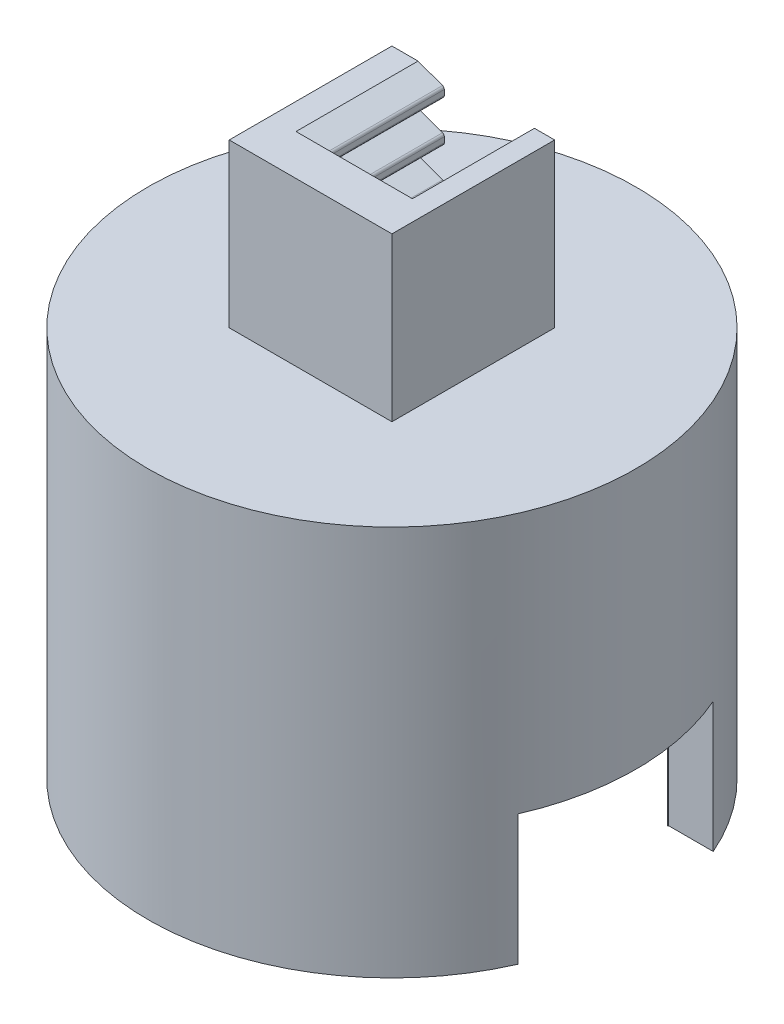
SolidWorks part; units mm, degrees
ref_plane "Front Plane" through (0, 0, 0) normal (0, 0, 1) x (1, 0, 0)
ref_plane "Top Plane" through (0, 0, 0) normal (0, 1, 0) x (1, 0, 0)
ref_plane "Right Plane" through (0, 0, 0) normal (1, 0, 0) x (0, 0, -1)
sketch "Sketch1" plane through (0, 0, 0) normal (0, 1, 0) x (1, 0, 0)
  circle A0 centre (0, 0) radius 15
  circle A1 centre (0, 0) radius 12.5
  dimension "D1" = 25
  dimension "D2" = 30
extrude "Boss-Extrude1" add sketch "Sketch1" along normal blind 20
sketch "Sketch2" plane through (0, 20, 0) normal (0, 1, 0) x (1, 0, 0)
  circle A0 centre (0, 0) radius 15
extrude "Boss-Extrude2" add sketch "Sketch2" along normal blind 4
ref_plane "Plane1" through (15, 0, 0) normal (1, 0, 0) x (0, 0, -1)
sketch "Sketch3" plane through (15, 0, 0) normal (1, 0, 0) x (0, 0, -1)
  line L0 (-15, 0) -> (15, 0) construction
  line L1 (-6, 0) -> (6, 0)
  line L2 (-6, 0) -> (-6, 8)
  line L3 (-6, 8) -> (6, 8)
  line L4 (6, 0) -> (6, 8)
  line L5 (0, 24) -> (0, 0) construction
  line L6 (15, 24) -> (-15, 24) construction
  dimension "D1" = 12
  dimension "D2" = 8
extrude "Cut-Extrude1" cut sketch "Sketch3" against normal blind 4
sketch "Sketch4" plane through (0, 24, 0) normal (0, 1, 0) x (1, 0, 0)
  line L0 (0, 5) -> (0, -5) construction
  line L1 (-5, 5) -> (5, 5)
  line L2 (-5, 5) -> (-5, -5)
  line L3 (-5, -5) -> (5, -5)
  line L4 (5, 5) -> (5, -5)
  line L5 (-5, 0) -> (5, 0) construction
  dimension "D1" = 10
  dimension "D2" = 10
extrude "Boss-Extrude3" add sketch "Sketch4" along normal blind 10
sketch "Sketch6" plane through (0, 0, -5) normal (0, 0, -1) x (-1, 0, 0)
  line L1 (-5, 34) -> (5, 34) construction
  line L3 (-3.7584, 34) -> (3.3958, 34)
  line L4 (-3.7584, 24) -> (3.5416, 24)
  line L405 (2.1355, 274) -> (0.2416, 274)
  line L406 (0.2416, 274) -> (0.2416, 34)
  line L407 (0.2416, 34) -> (-1.7584, 34)
  line L408 (-1.7584, 34) -> (-1.7584, 274)
  line L409 (-1.7584, 274) -> (-3.7584, 274)
  line L410 (-3.7584, 274) -> (-3.7584, 24)
  line L411 (-3.7584, 24) -> (3.5416, 24)
  line L412 (3.5416, 24) -> (3.5416, 24.6743)
  line L413 (3.5416, 24.6743) -> (1.8918, 25.2748)
  line L414 (1.7816, 25.432) -> (1.7816, 25.7555)
  line L415 (1.8918, 25.9128) -> (3.5416, 26.5133)
  line L416 (3.5416, 26.5133) -> (3.5416, 27.1876)
  line L417 (3.5416, 27.1876) -> (1.8918, 27.7881)
  line L418 (1.7816, 27.9453) -> (1.7816, 28.2688)
  line L419 (1.8918, 28.426) -> (3.5416, 29.0265)
  line L420 (3.5416, 29.0265) -> (3.5416, 29.7008)
  line L421 (3.5416, 29.7008) -> (1.8918, 30.3013)
  line L422 (1.7816, 30.4586) -> (1.7816, 30.7821)
  line L423 (1.8918, 30.9393) -> (3.5416, 31.5398)
  line L424 (3.5416, 31.5398) -> (3.5416, 32.2141)
  line L425 (3.5416, 32.2141) -> (1.8918, 32.8146)
  line L426 (1.7816, 32.9719) -> (1.7816, 33.2953)
  line L427 (1.8918, 33.4526) -> (3.5416, 34.0531)
  line L428 (3.5416, 34.0531) -> (3.5416, 34.7274)
  line L429 (3.5416, 34.7274) -> (1.8918, 35.3279)
  line L430 (1.7816, 35.4851) -> (1.7816, 35.8086)
  line L431 (1.8918, 35.9658) -> (3.5416, 36.5664)
  line L432 (3.5416, 36.5664) -> (3.5416, 37.2406)
  line L433 (3.5416, 37.2406) -> (1.8918, 37.8412)
  line L434 (1.7816, 37.9984) -> (1.7816, 38.3219)
  line L435 (1.8918, 38.4791) -> (3.5416, 39.0796)
  line L436 (3.5416, 39.0796) -> (3.5416, 39.7539)
  line L437 (3.5416, 39.7539) -> (1.8918, 40.3544)
  line L438 (1.7816, 40.5117) -> (1.7816, 40.8351)
  line L439 (1.8918, 40.9924) -> (3.5416, 41.5929)
  line L440 (3.5416, 41.5929) -> (3.5416, 42.2672)
  line L441 (3.5416, 42.2672) -> (1.8918, 42.8677)
  line L442 (1.7816, 43.025) -> (1.7816, 43.3484)
  line L443 (1.8918, 43.5057) -> (3.5416, 44.1062)
  line L444 (3.5416, 44.1062) -> (3.5416, 44.7805)
  line L445 (3.5416, 44.7805) -> (1.8918, 45.381)
  line L446 (1.7816, 45.5382) -> (1.7816, 45.8617)
  line L447 (1.8918, 46.0189) -> (3.5416, 46.6194)
  line L448 (3.5416, 46.6194) -> (3.5416, 47.2937)
  line L449 (3.5416, 47.2937) -> (1.8918, 47.8942)
  line L450 (1.7816, 48.0515) -> (1.7816, 48.375)
  line L451 (1.8918, 48.5322) -> (3.5416, 49.1327)
  line L452 (3.5416, 49.1327) -> (3.5416, 49.807)
  line L453 (3.5416, 49.807) -> (1.8918, 50.4075)
  line L454 (1.7816, 50.5648) -> (1.7816, 50.8882)
  line L455 (1.8918, 51.0455) -> (3.5416, 51.646)
  line L456 (3.5416, 51.646) -> (3.5416, 52.3203)
  line L457 (3.5416, 52.3203) -> (1.8918, 52.9208)
  line L458 (1.7816, 53.078) -> (1.7816, 53.4015)
  line L459 (1.8918, 53.5588) -> (3.5416, 54.1593)
  line L460 (3.5416, 54.1593) -> (3.5416, 54.8335)
  line L461 (3.5416, 54.8335) -> (1.8918, 55.4341)
  line L462 (1.7816, 55.5913) -> (1.7816, 55.9148)
  line L463 (1.8918, 56.072) -> (3.5416, 56.6725)
  line L464 (3.5416, 56.6725) -> (3.5416, 57.3468)
  line L465 (3.5416, 57.3468) -> (1.8918, 57.9473)
  line L466 (1.7816, 58.1046) -> (1.7816, 58.428)
  line L467 (1.8918, 58.5853) -> (3.5416, 59.1858)
  line L468 (3.5416, 59.1858) -> (3.5416, 59.8601)
  line L469 (3.5416, 59.8601) -> (1.8918, 60.4606)
  line L470 (1.7816, 60.6179) -> (1.7816, 60.9413)
  line L471 (1.8918, 61.0986) -> (3.5416, 61.6991)
  line L472 (3.5416, 61.6991) -> (3.5416, 62.3734)
  line L473 (3.5416, 62.3734) -> (1.8918, 62.9739)
  line L474 (1.7816, 63.1311) -> (1.7816, 63.4546)
  line L475 (1.8918, 63.6118) -> (3.5416, 64.2124)
  line L476 (3.5416, 64.2124) -> (3.5416, 64.8866)
  line L477 (3.5416, 64.8866) -> (1.8918, 65.4871)
  line L478 (1.7816, 65.6444) -> (1.7816, 65.9679)
  line L479 (1.8918, 66.1251) -> (3.5416, 66.7256)
  line L480 (3.5416, 66.7256) -> (3.5416, 67.3999)
  line L481 (3.5416, 67.3999) -> (1.8918, 68.0004)
  line L482 (1.7816, 68.1577) -> (1.7816, 68.4811)
  line L483 (1.8918, 68.6384) -> (3.5416, 69.2389)
  line L484 (3.5416, 69.2389) -> (3.5416, 69.9132)
  line L485 (3.5416, 69.9132) -> (1.8918, 70.5137)
  line L486 (1.7816, 70.6709) -> (1.7816, 70.9944)
  line L487 (1.8918, 71.1517) -> (3.5416, 71.7522)
  line L488 (3.5416, 71.7522) -> (3.5416, 72.4265)
  line L489 (3.5416, 72.4265) -> (1.8918, 73.027)
  line L490 (1.7816, 73.1842) -> (1.7816, 73.5077)
  line L491 (1.8918, 73.6649) -> (3.5416, 74.2654)
  line L492 (3.5416, 74.2654) -> (3.5416, 74.9397)
  line L493 (3.5416, 74.9397) -> (1.8918, 75.5402)
  line L494 (1.7816, 75.6975) -> (1.7816, 76.0209)
  line L495 (1.8918, 76.1782) -> (3.5416, 76.7787)
  line L496 (3.5416, 76.7787) -> (3.5416, 77.453)
  line L497 (3.5416, 77.453) -> (1.8918, 78.0535)
  line L498 (1.7816, 78.2108) -> (1.7816, 78.5342)
  line L499 (1.8918, 78.6915) -> (3.5416, 79.292)
  line L500 (3.5416, 79.292) -> (3.5416, 79.9663)
  line L501 (3.5416, 79.9663) -> (1.8918, 80.5668)
  line L502 (1.7816, 80.724) -> (1.7816, 81.0475)
  line L503 (1.8918, 81.2047) -> (3.5416, 81.8053)
  line L504 (3.5416, 81.8053) -> (3.5416, 82.4795)
  line L505 (3.5416, 82.4795) -> (1.8918, 83.0801)
  line L506 (1.7816, 83.2373) -> (1.7816, 83.5608)
  line L507 (1.8918, 83.718) -> (3.5416, 84.3185)
  line L508 (3.5416, 84.3185) -> (3.5416, 84.9928)
  line L509 (3.5416, 84.9928) -> (1.8918, 85.5933)
  line L510 (1.7816, 85.7506) -> (1.7816, 86.074)
  line L511 (1.8918, 86.2313) -> (3.5416, 86.8318)
  line L512 (3.5416, 86.8318) -> (3.5416, 87.5061)
  line L513 (3.5416, 87.5061) -> (1.8918, 88.1066)
  line L514 (1.7816, 88.2638) -> (1.7816, 88.5873)
  line L515 (1.8918, 88.7446) -> (3.5416, 89.3451)
  line L516 (3.5416, 89.3451) -> (3.5416, 90.0194)
  line L517 (3.5416, 90.0194) -> (1.8918, 90.6199)
  line L518 (1.7816, 90.7771) -> (1.7816, 91.1006)
  line L519 (1.8918, 91.2578) -> (3.5416, 91.8583)
  line L520 (3.5416, 91.8583) -> (3.5416, 92.5326)
  line L521 (3.5416, 92.5326) -> (1.8918, 93.1331)
  line L522 (1.7816, 93.2904) -> (1.7816, 93.6139)
  line L523 (1.8918, 93.7711) -> (3.5416, 94.3716)
  line L524 (3.5416, 94.3716) -> (3.5416, 95.0459)
  line L525 (3.5416, 95.0459) -> (1.8918, 95.6464)
  line L526 (1.7816, 95.8037) -> (1.7816, 96.1271)
  line L527 (1.8918, 96.2844) -> (3.5416, 96.8849)
  line L528 (3.5416, 96.8849) -> (3.5416, 97.5592)
  line L529 (3.5416, 97.5592) -> (1.8918, 98.1597)
  line L530 (1.7816, 98.3169) -> (1.7816, 98.6404)
  line L531 (1.8918, 98.7976) -> (3.5416, 99.3982)
  line L532 (3.5416, 99.3982) -> (3.5416, 100.0724)
  line L533 (3.5416, 100.0724) -> (1.8918, 100.673)
  line L534 (1.7816, 100.8302) -> (1.7816, 101.1537)
  line L535 (1.8918, 101.3109) -> (3.5416, 101.9114)
  line L536 (3.5416, 101.9114) -> (3.5416, 102.5857)
  line L537 (3.5416, 102.5857) -> (1.8918, 103.1862)
  line L538 (1.7816, 103.3435) -> (1.7816, 103.6669)
  line L539 (1.8918, 103.8242) -> (3.5416, 104.4247)
  line L540 (3.5416, 104.4247) -> (3.5416, 105.099)
  line L541 (3.5416, 105.099) -> (1.8918, 105.6995)
  line L542 (1.7816, 105.8568) -> (1.7816, 106.1802)
  line L543 (1.8918, 106.3375) -> (3.5416, 106.938)
  line L544 (3.5416, 106.938) -> (3.5416, 107.6123)
  line L545 (3.5416, 107.6123) -> (1.8918, 108.2128)
  line L546 (1.7816, 108.37) -> (1.7816, 108.6935)
  line L547 (1.8918, 108.8507) -> (3.5416, 109.4512)
  line L548 (3.5416, 109.4512) -> (3.5416, 110.1255)
  line L549 (3.5416, 110.1255) -> (1.8918, 110.726)
  line L550 (1.7816, 110.8833) -> (1.7816, 111.2068)
  line L551 (1.8918, 111.364) -> (3.5416, 111.9645)
  line L552 (3.5416, 111.9645) -> (3.5416, 112.6388)
  line L553 (3.5416, 112.6388) -> (1.8918, 113.2393)
  line L554 (1.7816, 113.3966) -> (1.7816, 113.72)
  line L555 (1.8918, 113.8773) -> (3.5416, 114.4778)
  line L556 (3.5416, 114.4778) -> (3.5416, 115.1521)
  line L557 (3.5416, 115.1521) -> (1.8918, 115.7526)
  line L558 (1.7816, 115.9098) -> (1.7816, 116.2333)
  line L559 (1.8918, 116.3906) -> (3.5416, 116.9911)
  line L560 (3.5416, 116.9911) -> (3.5416, 117.6653)
  line L561 (3.5416, 117.6653) -> (1.8918, 118.2659)
  line L562 (1.7816, 118.4231) -> (1.7816, 118.7466)
  line L563 (1.8918, 118.9038) -> (3.5416, 119.5043)
  line L564 (3.5416, 119.5043) -> (3.5416, 120.1786)
  line L565 (3.5416, 120.1786) -> (1.8918, 120.7791)
  line L566 (1.7816, 120.9364) -> (1.7816, 121.2598)
  line L567 (1.8918, 121.4171) -> (3.5416, 122.0176)
  line L568 (3.5416, 122.0176) -> (3.5416, 122.6919)
  line L569 (3.5416, 122.6919) -> (1.8918, 123.2924)
  line L570 (1.7816, 123.4497) -> (1.7816, 123.7731)
  line L571 (1.8918, 123.9304) -> (3.5416, 124.5309)
  line L572 (3.5416, 124.5309) -> (3.5416, 125.2052)
  line L573 (3.5416, 125.2052) -> (1.8918, 125.8057)
  line L574 (1.7816, 125.9629) -> (1.7816, 126.2864)
  line L575 (1.8918, 126.4436) -> (3.5416, 127.0442)
  line L576 (3.5416, 127.0442) -> (3.5416, 127.7184)
  line L577 (3.5416, 127.7184) -> (1.8918, 128.3189)
  line L578 (1.7816, 128.4762) -> (1.7816, 128.7997)
  line L579 (1.8918, 128.9569) -> (3.5416, 129.5574)
  line L580 (3.5416, 129.5574) -> (3.5416, 130.2317)
  line L581 (3.5416, 130.2317) -> (1.8918, 130.8322)
  line L582 (1.7816, 130.9895) -> (1.7816, 131.3129)
  line L583 (1.8918, 131.4702) -> (3.5416, 132.0707)
  line L584 (3.5416, 132.0707) -> (3.5416, 132.745)
  line L585 (3.5416, 132.745) -> (1.8918, 133.3455)
  line L586 (1.7816, 133.5027) -> (1.7816, 133.8262)
  line L587 (1.8918, 133.9835) -> (3.5416, 134.584)
  line L588 (3.5416, 134.584) -> (3.5416, 135.2583)
  line L589 (3.5416, 135.2583) -> (1.8918, 135.8588)
  line L590 (1.7816, 136.016) -> (1.7816, 136.3395)
  line L591 (1.8918, 136.4967) -> (3.5416, 137.0972)
  line L592 (3.5416, 137.0972) -> (3.5416, 137.7715)
  line L593 (3.5416, 137.7715) -> (1.8918, 138.372)
  line L594 (1.7816, 138.5293) -> (1.7816, 138.8527)
  line L595 (1.8918, 139.01) -> (3.5416, 139.6105)
  line L596 (3.5416, 139.6105) -> (3.5416, 140.2848)
  line L597 (3.5416, 140.2848) -> (1.8918, 140.8853)
  line L598 (1.7816, 141.0426) -> (1.7816, 141.366)
  line L599 (1.8918, 141.5233) -> (3.5416, 142.1238)
  line L600 (3.5416, 142.1238) -> (3.5416, 142.7981)
  line L601 (3.5416, 142.7981) -> (1.8918, 143.3986)
  line L602 (1.7816, 143.5558) -> (1.7816, 143.8793)
  line L603 (1.8918, 144.0365) -> (3.5416, 144.6371)
  line L604 (3.5416, 144.6371) -> (3.5416, 145.3113)
  line L605 (3.5416, 145.3113) -> (1.8918, 145.9119)
  line L606 (1.7816, 146.0691) -> (1.7816, 146.3926)
  line L607 (1.8918, 146.5498) -> (3.5416, 147.1503)
  line L608 (3.5416, 147.1503) -> (3.5416, 147.8246)
  line L609 (3.5416, 147.8246) -> (1.8918, 148.4251)
  line L610 (1.7816, 148.5824) -> (1.7816, 148.9058)
  line L611 (1.8918, 149.0631) -> (3.5416, 149.6636)
  line L612 (3.5416, 149.6636) -> (3.5416, 150.3379)
  line L613 (3.5416, 150.3379) -> (1.8918, 150.9384)
  line L614 (1.7816, 151.0956) -> (1.7816, 151.4191)
  line L615 (1.8918, 151.5764) -> (3.5416, 152.1769)
  line L616 (3.5416, 152.1769) -> (3.5416, 152.8512)
  line L617 (3.5416, 152.8512) -> (1.8918, 153.4517)
  line L618 (1.7816, 153.6089) -> (1.7816, 153.9324)
  line L619 (1.8918, 154.0896) -> (3.5416, 154.6901)
  line L620 (3.5416, 154.6901) -> (3.5416, 155.3644)
  line L621 (3.5416, 155.3644) -> (1.8918, 155.9649)
  line L622 (1.7816, 156.1222) -> (1.7816, 156.4457)
  line L623 (1.8918, 156.6029) -> (3.5416, 157.2034)
  line L624 (3.5416, 157.2034) -> (3.5416, 157.8777)
  line L625 (3.5416, 157.8777) -> (1.8918, 158.4782)
  line L626 (1.7816, 158.6355) -> (1.7816, 158.9589)
  line L627 (1.8918, 159.1162) -> (3.5416, 159.7167)
  line L628 (3.5416, 159.7167) -> (3.5416, 160.391)
  line L629 (3.5416, 160.391) -> (1.8918, 160.9915)
  line L630 (1.7816, 161.1487) -> (1.7816, 161.4722)
  line L631 (1.8918, 161.6294) -> (3.5416, 162.23)
  line L632 (3.5416, 162.23) -> (3.5416, 162.9042)
  line L633 (3.5416, 162.9042) -> (1.8918, 163.5048)
  line L634 (1.7816, 163.662) -> (1.7816, 163.9855)
  line L635 (1.8918, 164.1427) -> (3.5416, 164.7432)
  line L636 (3.5416, 164.7432) -> (3.5416, 165.4175)
  line L637 (3.5416, 165.4175) -> (1.8918, 166.018)
  line L638 (1.7816, 166.1753) -> (1.7816, 166.4987)
  line L639 (1.8918, 166.656) -> (3.5416, 167.2565)
  line L640 (3.5416, 167.2565) -> (3.5416, 167.9308)
  line L641 (3.5416, 167.9308) -> (1.8918, 168.5313)
  line L642 (1.7816, 168.6886) -> (1.7816, 169.012)
  line L643 (1.8918, 169.1693) -> (3.5416, 169.7698)
  line L644 (3.5416, 169.7698) -> (3.5416, 170.4441)
  line L645 (3.5416, 170.4441) -> (1.8918, 171.0446)
  line L646 (1.7816, 171.2018) -> (1.7816, 171.5253)
  line L647 (1.8918, 171.6825) -> (3.5416, 172.283)
  line L648 (3.5416, 172.283) -> (3.5416, 172.9573)
  line L649 (3.5416, 172.9573) -> (1.8918, 173.5578)
  line L650 (1.7816, 173.7151) -> (1.7816, 174.0386)
  line L651 (1.8918, 174.1958) -> (3.5416, 174.7963)
  line L652 (3.5416, 174.7963) -> (3.5416, 175.4706)
  line L653 (3.5416, 175.4706) -> (1.8918, 176.0711)
  line L654 (1.7816, 176.2284) -> (1.7816, 176.5518)
  line L655 (1.8918, 176.7091) -> (3.5416, 177.3096)
  line L656 (3.5416, 177.3096) -> (3.5416, 177.9839)
  line L657 (3.5416, 177.9839) -> (1.8918, 178.5844)
  line L658 (1.7816, 178.7416) -> (1.7816, 179.0651)
  line L659 (1.8918, 179.2224) -> (3.5416, 179.8229)
  line L660 (3.5416, 179.8229) -> (3.5416, 180.4971)
  line L661 (3.5416, 180.4971) -> (1.8918, 181.0977)
  line L662 (1.7816, 181.2549) -> (1.7816, 181.5784)
  line L663 (1.8918, 181.7356) -> (3.5416, 182.3361)
  line L664 (3.5416, 182.3361) -> (3.5416, 183.0104)
  line L665 (3.5416, 183.0104) -> (1.8918, 183.6109)
  line L666 (1.7816, 183.7682) -> (1.7816, 184.0916)
  line L667 (1.8918, 184.2489) -> (3.5416, 184.8494)
  line L668 (3.5416, 184.8494) -> (3.5416, 185.5237)
  line L669 (3.5416, 185.5237) -> (1.8918, 186.1242)
  line L670 (1.7816, 186.2815) -> (1.7816, 186.6049)
  line L671 (1.8918, 186.7622) -> (3.5416, 187.3627)
  line L672 (3.5416, 187.3627) -> (3.5416, 188.037)
  line L673 (3.5416, 188.037) -> (1.8918, 188.6375)
  line L674 (1.7816, 188.7947) -> (1.7816, 189.1182)
  line L675 (1.8918, 189.2754) -> (3.5416, 189.876)
  line L676 (3.5416, 189.876) -> (3.5416, 190.5502)
  line L677 (3.5416, 190.5502) -> (1.8918, 191.1507)
  line L678 (1.7816, 191.308) -> (1.7816, 191.6315)
  line L679 (1.8918, 191.7887) -> (3.5416, 192.3892)
  line L680 (3.5416, 192.3892) -> (3.5416, 193.0635)
  line L681 (3.5416, 193.0635) -> (1.8918, 193.664)
  line L682 (1.7816, 193.8213) -> (1.7816, 194.1447)
  line L683 (1.8918, 194.302) -> (3.5416, 194.9025)
  line L684 (3.5416, 194.9025) -> (3.5416, 195.5768)
  line L685 (3.5416, 195.5768) -> (1.8918, 196.1773)
  line L686 (1.7816, 196.3345) -> (1.7816, 196.658)
  line L687 (1.8918, 196.8153) -> (3.5416, 197.4158)
  line L688 (3.5416, 197.4158) -> (3.5416, 198.0901)
  line L689 (3.5416, 198.0901) -> (1.8918, 198.6906)
  line L690 (1.7816, 198.8478) -> (1.7816, 199.1713)
  line L691 (1.8918, 199.3285) -> (3.5416, 199.929)
  line L692 (3.5416, 199.929) -> (3.5416, 200.6033)
  line L693 (3.5416, 200.6033) -> (1.8918, 201.2038)
  line L694 (1.7816, 201.3611) -> (1.7816, 201.6845)
  line L695 (1.8918, 201.8418) -> (3.5416, 202.4423)
  line L696 (3.5416, 202.4423) -> (3.5416, 203.1166)
  line L697 (3.5416, 203.1166) -> (1.8918, 203.7171)
  line L698 (1.7816, 203.8744) -> (1.7816, 204.1978)
  line L699 (1.8918, 204.3551) -> (3.5416, 204.9556)
  line L700 (3.5416, 204.9556) -> (3.5416, 205.6299)
  line L701 (3.5416, 205.6299) -> (1.8918, 206.2304)
  line L702 (1.7816, 206.3876) -> (1.7816, 206.7111)
  line L703 (1.8918, 206.8683) -> (3.5416, 207.4689)
  line L704 (3.5416, 207.4689) -> (3.5416, 208.1431)
  line L705 (3.5416, 208.1431) -> (1.8918, 208.7437)
  line L706 (1.7816, 208.9009) -> (1.7816, 209.2244)
  line L707 (1.8918, 209.3816) -> (3.5416, 209.9821)
  line L708 (3.5416, 209.9821) -> (3.5416, 210.6564)
  line L709 (3.5416, 210.6564) -> (1.8918, 211.2569)
  line L710 (1.7816, 211.4142) -> (1.7816, 211.7376)
  line L711 (1.8918, 211.8949) -> (3.5416, 212.4954)
  line L712 (3.5416, 212.4954) -> (3.5416, 213.1697)
  line L713 (3.5416, 213.1697) -> (1.8918, 213.7702)
  line L714 (1.7816, 213.9274) -> (1.7816, 214.2509)
  line L715 (1.8918, 214.4082) -> (3.5416, 215.0087)
  line L716 (3.5416, 215.0087) -> (3.5416, 215.683)
  line L717 (3.5416, 215.683) -> (1.8918, 216.2835)
  line L718 (1.7816, 216.4407) -> (1.7816, 216.7642)
  line L719 (1.8918, 216.9214) -> (3.5416, 217.5219)
  line L720 (3.5416, 217.5219) -> (3.5416, 218.1962)
  line L721 (3.5416, 218.1962) -> (1.8918, 218.7967)
  line L722 (1.7816, 218.954) -> (1.7816, 219.2775)
  line L723 (1.8918, 219.4347) -> (3.5416, 220.0352)
  line L724 (3.5416, 220.0352) -> (3.5416, 220.7095)
  line L725 (3.5416, 220.7095) -> (1.8918, 221.31)
  line L726 (1.7816, 221.4673) -> (1.7816, 221.7907)
  line L727 (1.8918, 221.948) -> (3.5416, 222.5485)
  line L728 (3.5416, 222.5485) -> (3.5416, 223.2228)
  line L729 (3.5416, 223.2228) -> (1.8918, 223.8233)
  line L730 (1.7816, 223.9805) -> (1.7816, 224.304)
  line L731 (1.8918, 224.4612) -> (3.5416, 225.0618)
  line L732 (3.5416, 225.0618) -> (3.5416, 225.736)
  line L733 (3.5416, 225.736) -> (1.8918, 226.3366)
  line L734 (1.7816, 226.4938) -> (1.7816, 226.8173)
  line L735 (1.8918, 226.9745) -> (3.5416, 227.575)
  line L736 (3.5416, 227.575) -> (3.5416, 228.2493)
  line L737 (3.5416, 228.2493) -> (1.8918, 228.8498)
  line L738 (1.7816, 229.0071) -> (1.7816, 229.3305)
  line L739 (1.8918, 229.4878) -> (3.5416, 230.0883)
  line L740 (3.5416, 230.0883) -> (3.5416, 230.7626)
  line L741 (3.5416, 230.7626) -> (1.8918, 231.3631)
  line L742 (1.7816, 231.5204) -> (1.7816, 231.8438)
  line L743 (1.8918, 232.0011) -> (3.5416, 232.6016)
  line L744 (3.5416, 232.6016) -> (3.5416, 233.2759)
  line L745 (3.5416, 233.2759) -> (1.8918, 233.8764)
  line L746 (1.7816, 234.0336) -> (1.7816, 234.3571)
  line L747 (1.8918, 234.5143) -> (3.5416, 235.1148)
  line L748 (3.5416, 235.1148) -> (3.5416, 235.7891)
  line L749 (3.5416, 235.7891) -> (1.8918, 236.3896)
  line L750 (1.7816, 236.5469) -> (1.7816, 236.8704)
  line L751 (1.8918, 237.0276) -> (3.5416, 237.6281)
  line L752 (3.5416, 237.6281) -> (3.5416, 238.3024)
  line L753 (3.5416, 238.3024) -> (1.8918, 238.9029)
  line L754 (1.7816, 239.0602) -> (1.7816, 239.3836)
  line L755 (1.8918, 239.5409) -> (3.5416, 240.1414)
  line L756 (3.5416, 240.1414) -> (3.5416, 240.8157)
  line L757 (3.5416, 240.8157) -> (1.8918, 241.4162)
  line L758 (1.7816, 241.5734) -> (1.7816, 241.8969)
  line L759 (1.8918, 242.0542) -> (3.5416, 242.6547)
  line L760 (3.5416, 242.6547) -> (3.5416, 243.3289)
  line L761 (3.5416, 243.3289) -> (1.8918, 243.9295)
  line L762 (1.7816, 244.0867) -> (1.7816, 244.4102)
  line L763 (1.8918, 244.5674) -> (3.5416, 245.1679)
  line L764 (3.5416, 245.1679) -> (3.5416, 245.8422)
  line L765 (3.5416, 245.8422) -> (1.8918, 246.4427)
  line L766 (1.7816, 246.6) -> (1.7816, 246.9234)
  line L767 (1.8918, 247.0807) -> (3.5416, 247.6812)
  line L768 (3.5416, 247.6812) -> (3.5416, 248.3555)
  line L769 (3.5416, 248.3555) -> (1.8918, 248.956)
  line L770 (1.7816, 249.1133) -> (1.7816, 249.4367)
  line L771 (1.8918, 249.594) -> (3.5416, 250.1945)
  line L772 (3.5416, 250.1945) -> (3.5416, 250.8688)
  line L773 (3.5416, 250.8688) -> (1.8918, 251.4693)
  line L774 (1.7816, 251.6265) -> (1.7816, 251.95)
  line L775 (1.8918, 252.1072) -> (3.5416, 252.7078)
  line L776 (3.5416, 252.7078) -> (3.5416, 253.382)
  line L777 (3.5416, 253.382) -> (1.8918, 253.9825)
  line L778 (1.7816, 254.1398) -> (1.7816, 254.4633)
  line L779 (1.8918, 254.6205) -> (3.5416, 255.221)
  line L780 (3.5416, 255.221) -> (3.5416, 255.8953)
  line L781 (3.5416, 255.8953) -> (1.8918, 256.4958)
  line L782 (1.7816, 256.6531) -> (1.7816, 256.9765)
  line L783 (1.8918, 257.1338) -> (3.5416, 257.7343)
  line L784 (3.5416, 257.7343) -> (3.5416, 258.4086)
  line L785 (3.5416, 258.4086) -> (1.8918, 259.0091)
  line L786 (1.7816, 259.1663) -> (1.7816, 259.4898)
  line L787 (1.8918, 259.6471) -> (3.5416, 260.2476)
  line L788 (3.5416, 260.2476) -> (3.5416, 260.9219)
  line L789 (3.5416, 260.9219) -> (1.8918, 261.5224)
  line L790 (1.7816, 261.6796) -> (1.7816, 262.0031)
  line L791 (1.8918, 262.1603) -> (3.5416, 262.7608)
  line L792 (3.5416, 262.7608) -> (3.5416, 263.4351)
  line L793 (3.5416, 263.4351) -> (1.8918, 264.0356)
  line L794 (1.7816, 264.1929) -> (1.7816, 264.5163)
  line L795 (1.8918, 264.6736) -> (3.5416, 265.2741)
  line L796 (3.5416, 265.2741) -> (3.5416, 265.9484)
  line L797 (3.5416, 265.9484) -> (1.8918, 266.5489)
  line L798 (1.7816, 266.7062) -> (1.7816, 267.0296)
  line L799 (1.8918, 267.1869) -> (3.5416, 267.7874)
  line L800 (3.5416, 267.7874) -> (3.5416, 268.4617)
  line L801 (3.5416, 268.4617) -> (1.8918, 269.0622)
  line L802 (1.7816, 269.2194) -> (1.7816, 269.5429)
  line L803 (1.8918, 269.7001) -> (3.5416, 270.3007)
  line L804 (3.5416, 270.3007) -> (3.5416, 270.9749)
  line L805 (3.5416, 270.9749) -> (1.8918, 271.5755)
  line L806 (1.7816, 271.7327) -> (1.7816, 272.0562)
  line L807 (1.8918, 272.2134) -> (3.5416, 272.8139)
  line L808 (3.5416, 272.8139) -> (3.5416, 273.4882)
  line L809 (3.5416, 273.4882) -> (2.1355, 274)
  line L815 (-3.7584, 34) -> (-3.7584, 24)
  line L816 (-3.7584, 24) -> (3.5416, 24)
  line L817 (3.5416, 24) -> (3.5416, 24.6743)
  line L818 (3.5416, 24.6743) -> (1.8918, 25.2748)
  line L819 (1.7816, 25.432) -> (1.7816, 25.7555)
  line L820 (1.8918, 25.9128) -> (3.5416, 26.5133)
  line L821 (3.5416, 26.5133) -> (3.5416, 27.1876)
  line L822 (3.5416, 27.1876) -> (1.8918, 27.7881)
  line L823 (1.7816, 27.9453) -> (1.7816, 28.2688)
  line L824 (1.8918, 28.426) -> (3.5416, 29.0265)
  line L825 (3.5416, 29.0265) -> (3.5416, 29.7008)
  line L826 (3.5416, 29.7008) -> (1.8918, 30.3013)
  line L827 (1.7816, 30.4586) -> (1.7816, 30.7821)
  line L828 (1.8918, 30.9393) -> (3.5416, 31.5398)
  line L829 (3.5416, 31.5398) -> (3.5416, 32.2141)
  line L830 (3.5416, 32.2141) -> (1.8918, 32.8146)
  line L831 (1.7816, 32.9719) -> (1.7816, 33.2953)
  line L832 (1.8918, 33.4526) -> (3.3958, 34)
  arc A198 (1.7816, 25.432) -> (1.8918, 25.2748) centre (1.949, 25.432) ccw
  arc A199 (1.8918, 25.9128) -> (1.7816, 25.7555) centre (1.949, 25.7555) ccw
  arc A200 (1.7816, 27.9453) -> (1.8918, 27.7881) centre (1.949, 27.9453) ccw
  arc A201 (1.8918, 28.426) -> (1.7816, 28.2688) centre (1.949, 28.2688) ccw
  arc A202 (1.7816, 30.4586) -> (1.8918, 30.3013) centre (1.949, 30.4586) ccw
  arc A203 (1.8918, 30.9393) -> (1.7816, 30.7821) centre (1.949, 30.7821) ccw
  arc A204 (1.7816, 32.9719) -> (1.8918, 32.8146) centre (1.949, 32.9719) ccw
  arc A205 (1.8918, 33.4526) -> (1.7816, 33.2953) centre (1.949, 33.2953) ccw
  arc A206 (1.7816, 35.4851) -> (1.8918, 35.3279) centre (1.949, 35.4851) ccw
  arc A207 (1.8918, 35.9658) -> (1.7816, 35.8086) centre (1.949, 35.8086) ccw
  arc A208 (1.7816, 37.9984) -> (1.8918, 37.8412) centre (1.949, 37.9984) ccw
  arc A209 (1.8918, 38.4791) -> (1.7816, 38.3219) centre (1.949, 38.3219) ccw
  arc A210 (1.7816, 40.5117) -> (1.8918, 40.3544) centre (1.949, 40.5117) ccw
  arc A211 (1.8918, 40.9924) -> (1.7816, 40.8351) centre (1.949, 40.8351) ccw
  arc A212 (1.7816, 43.025) -> (1.8918, 42.8677) centre (1.949, 43.025) ccw
  arc A213 (1.8918, 43.5057) -> (1.7816, 43.3484) centre (1.949, 43.3484) ccw
  arc A214 (1.7816, 45.5382) -> (1.8918, 45.381) centre (1.949, 45.5382) ccw
  arc A215 (1.8918, 46.0189) -> (1.7816, 45.8617) centre (1.949, 45.8617) ccw
  arc A216 (1.7816, 48.0515) -> (1.8918, 47.8942) centre (1.949, 48.0515) ccw
  arc A217 (1.8918, 48.5322) -> (1.7816, 48.375) centre (1.949, 48.375) ccw
  arc A218 (1.7816, 50.5648) -> (1.8918, 50.4075) centre (1.949, 50.5648) ccw
  arc A219 (1.8918, 51.0455) -> (1.7816, 50.8882) centre (1.949, 50.8882) ccw
  arc A220 (1.7816, 53.078) -> (1.8918, 52.9208) centre (1.949, 53.078) ccw
  arc A221 (1.8918, 53.5588) -> (1.7816, 53.4015) centre (1.949, 53.4015) ccw
  arc A222 (1.7816, 55.5913) -> (1.8918, 55.4341) centre (1.949, 55.5913) ccw
  arc A223 (1.8918, 56.072) -> (1.7816, 55.9148) centre (1.949, 55.9148) ccw
  arc A224 (1.7816, 58.1046) -> (1.8918, 57.9473) centre (1.949, 58.1046) ccw
  arc A225 (1.8918, 58.5853) -> (1.7816, 58.428) centre (1.949, 58.428) ccw
  arc A226 (1.7816, 60.6179) -> (1.8918, 60.4606) centre (1.949, 60.6179) ccw
  arc A227 (1.8918, 61.0986) -> (1.7816, 60.9413) centre (1.949, 60.9413) ccw
  arc A228 (1.7816, 63.1311) -> (1.8918, 62.9739) centre (1.949, 63.1311) ccw
  arc A229 (1.8918, 63.6118) -> (1.7816, 63.4546) centre (1.949, 63.4546) ccw
  arc A230 (1.7816, 65.6444) -> (1.8918, 65.4871) centre (1.949, 65.6444) ccw
  arc A231 (1.8918, 66.1251) -> (1.7816, 65.9679) centre (1.949, 65.9679) ccw
  arc A232 (1.7816, 68.1577) -> (1.8918, 68.0004) centre (1.949, 68.1577) ccw
  arc A233 (1.8918, 68.6384) -> (1.7816, 68.4811) centre (1.949, 68.4811) ccw
  arc A234 (1.7816, 70.6709) -> (1.8918, 70.5137) centre (1.949, 70.6709) ccw
  arc A235 (1.8918, 71.1517) -> (1.7816, 70.9944) centre (1.949, 70.9944) ccw
  arc A236 (1.7816, 73.1842) -> (1.8918, 73.027) centre (1.949, 73.1842) ccw
  arc A237 (1.8918, 73.6649) -> (1.7816, 73.5077) centre (1.949, 73.5077) ccw
  arc A238 (1.7816, 75.6975) -> (1.8918, 75.5402) centre (1.949, 75.6975) ccw
  arc A239 (1.8918, 76.1782) -> (1.7816, 76.0209) centre (1.949, 76.0209) ccw
  arc A240 (1.7816, 78.2108) -> (1.8918, 78.0535) centre (1.949, 78.2108) ccw
  arc A241 (1.8918, 78.6915) -> (1.7816, 78.5342) centre (1.949, 78.5342) ccw
  arc A242 (1.7816, 80.724) -> (1.8918, 80.5668) centre (1.949, 80.724) ccw
  arc A243 (1.8918, 81.2047) -> (1.7816, 81.0475) centre (1.949, 81.0475) ccw
  arc A244 (1.7816, 83.2373) -> (1.8918, 83.0801) centre (1.949, 83.2373) ccw
  arc A245 (1.8918, 83.718) -> (1.7816, 83.5608) centre (1.949, 83.5608) ccw
  arc A246 (1.7816, 85.7506) -> (1.8918, 85.5933) centre (1.949, 85.7506) ccw
  arc A247 (1.8918, 86.2313) -> (1.7816, 86.074) centre (1.949, 86.074) ccw
  arc A248 (1.7816, 88.2638) -> (1.8918, 88.1066) centre (1.949, 88.2638) ccw
  arc A249 (1.8918, 88.7446) -> (1.7816, 88.5873) centre (1.949, 88.5873) ccw
  arc A250 (1.7816, 90.7771) -> (1.8918, 90.6199) centre (1.949, 90.7771) ccw
  arc A251 (1.8918, 91.2578) -> (1.7816, 91.1006) centre (1.949, 91.1006) ccw
  arc A252 (1.7816, 93.2904) -> (1.8918, 93.1331) centre (1.949, 93.2904) ccw
  arc A253 (1.8918, 93.7711) -> (1.7816, 93.6139) centre (1.949, 93.6139) ccw
  arc A254 (1.7816, 95.8037) -> (1.8918, 95.6464) centre (1.949, 95.8037) ccw
  arc A255 (1.8918, 96.2844) -> (1.7816, 96.1271) centre (1.949, 96.1271) ccw
  arc A256 (1.7816, 98.3169) -> (1.8918, 98.1597) centre (1.949, 98.3169) ccw
  arc A257 (1.8918, 98.7976) -> (1.7816, 98.6404) centre (1.949, 98.6404) ccw
  arc A258 (1.7816, 100.8302) -> (1.8918, 100.673) centre (1.949, 100.8302) ccw
  arc A259 (1.8918, 101.3109) -> (1.7816, 101.1537) centre (1.949, 101.1537) ccw
  arc A260 (1.7816, 103.3435) -> (1.8918, 103.1862) centre (1.949, 103.3435) ccw
  arc A261 (1.8918, 103.8242) -> (1.7816, 103.6669) centre (1.949, 103.6669) ccw
  arc A262 (1.7816, 105.8568) -> (1.8918, 105.6995) centre (1.949, 105.8568) ccw
  arc A263 (1.8918, 106.3375) -> (1.7816, 106.1802) centre (1.949, 106.1802) ccw
  arc A264 (1.7816, 108.37) -> (1.8918, 108.2128) centre (1.949, 108.37) ccw
  arc A265 (1.8918, 108.8507) -> (1.7816, 108.6935) centre (1.949, 108.6935) ccw
  arc A266 (1.7816, 110.8833) -> (1.8918, 110.726) centre (1.949, 110.8833) ccw
  arc A267 (1.8918, 111.364) -> (1.7816, 111.2068) centre (1.949, 111.2068) ccw
  arc A268 (1.7816, 113.3966) -> (1.8918, 113.2393) centre (1.949, 113.3966) ccw
  arc A269 (1.8918, 113.8773) -> (1.7816, 113.72) centre (1.949, 113.72) ccw
  arc A270 (1.7816, 115.9098) -> (1.8918, 115.7526) centre (1.949, 115.9098) ccw
  arc A271 (1.8918, 116.3906) -> (1.7816, 116.2333) centre (1.949, 116.2333) ccw
  arc A272 (1.7816, 118.4231) -> (1.8918, 118.2659) centre (1.949, 118.4231) ccw
  arc A273 (1.8918, 118.9038) -> (1.7816, 118.7466) centre (1.949, 118.7466) ccw
  arc A274 (1.7816, 120.9364) -> (1.8918, 120.7791) centre (1.949, 120.9364) ccw
  arc A275 (1.8918, 121.4171) -> (1.7816, 121.2598) centre (1.949, 121.2598) ccw
  arc A276 (1.7816, 123.4497) -> (1.8918, 123.2924) centre (1.949, 123.4497) ccw
  arc A277 (1.8918, 123.9304) -> (1.7816, 123.7731) centre (1.949, 123.7731) ccw
  arc A278 (1.7816, 125.9629) -> (1.8918, 125.8057) centre (1.949, 125.9629) ccw
  arc A279 (1.8918, 126.4436) -> (1.7816, 126.2864) centre (1.949, 126.2864) ccw
  arc A280 (1.7816, 128.4762) -> (1.8918, 128.3189) centre (1.949, 128.4762) ccw
  arc A281 (1.8918, 128.9569) -> (1.7816, 128.7997) centre (1.949, 128.7997) ccw
  arc A282 (1.7816, 130.9895) -> (1.8918, 130.8322) centre (1.949, 130.9895) ccw
  arc A283 (1.8918, 131.4702) -> (1.7816, 131.3129) centre (1.949, 131.3129) ccw
  arc A284 (1.7816, 133.5027) -> (1.8918, 133.3455) centre (1.949, 133.5027) ccw
  arc A285 (1.8918, 133.9835) -> (1.7816, 133.8262) centre (1.949, 133.8262) ccw
  arc A286 (1.7816, 136.016) -> (1.8918, 135.8588) centre (1.949, 136.016) ccw
  arc A287 (1.8918, 136.4967) -> (1.7816, 136.3395) centre (1.949, 136.3395) ccw
  arc A288 (1.7816, 138.5293) -> (1.8918, 138.372) centre (1.949, 138.5293) ccw
  arc A289 (1.8918, 139.01) -> (1.7816, 138.8527) centre (1.949, 138.8527) ccw
  arc A290 (1.7816, 141.0426) -> (1.8918, 140.8853) centre (1.949, 141.0426) ccw
  arc A291 (1.8918, 141.5233) -> (1.7816, 141.366) centre (1.949, 141.366) ccw
  arc A292 (1.7816, 143.5558) -> (1.8918, 143.3986) centre (1.949, 143.5558) ccw
  arc A293 (1.8918, 144.0365) -> (1.7816, 143.8793) centre (1.949, 143.8793) ccw
  arc A294 (1.7816, 146.0691) -> (1.8918, 145.9119) centre (1.949, 146.0691) ccw
  arc A295 (1.8918, 146.5498) -> (1.7816, 146.3926) centre (1.949, 146.3926) ccw
  arc A296 (1.7816, 148.5824) -> (1.8918, 148.4251) centre (1.949, 148.5824) ccw
  arc A297 (1.8918, 149.0631) -> (1.7816, 148.9058) centre (1.949, 148.9058) ccw
  arc A298 (1.7816, 151.0956) -> (1.8918, 150.9384) centre (1.949, 151.0956) ccw
  arc A299 (1.8918, 151.5764) -> (1.7816, 151.4191) centre (1.949, 151.4191) ccw
  arc A300 (1.7816, 153.6089) -> (1.8918, 153.4517) centre (1.949, 153.6089) ccw
  arc A301 (1.8918, 154.0896) -> (1.7816, 153.9324) centre (1.949, 153.9324) ccw
  arc A302 (1.7816, 156.1222) -> (1.8918, 155.9649) centre (1.949, 156.1222) ccw
  arc A303 (1.8918, 156.6029) -> (1.7816, 156.4457) centre (1.949, 156.4457) ccw
  arc A304 (1.7816, 158.6355) -> (1.8918, 158.4782) centre (1.949, 158.6355) ccw
  arc A305 (1.8918, 159.1162) -> (1.7816, 158.9589) centre (1.949, 158.9589) ccw
  arc A306 (1.7816, 161.1487) -> (1.8918, 160.9915) centre (1.949, 161.1487) ccw
  arc A307 (1.8918, 161.6294) -> (1.7816, 161.4722) centre (1.949, 161.4722) ccw
  arc A308 (1.7816, 163.662) -> (1.8918, 163.5048) centre (1.949, 163.662) ccw
  arc A309 (1.8918, 164.1427) -> (1.7816, 163.9855) centre (1.949, 163.9855) ccw
  arc A310 (1.7816, 166.1753) -> (1.8918, 166.018) centre (1.949, 166.1753) ccw
  arc A311 (1.8918, 166.656) -> (1.7816, 166.4987) centre (1.949, 166.4987) ccw
  arc A312 (1.7816, 168.6886) -> (1.8918, 168.5313) centre (1.949, 168.6886) ccw
  arc A313 (1.8918, 169.1693) -> (1.7816, 169.012) centre (1.949, 169.012) ccw
  arc A314 (1.7816, 171.2018) -> (1.8918, 171.0446) centre (1.949, 171.2018) ccw
  arc A315 (1.8918, 171.6825) -> (1.7816, 171.5253) centre (1.949, 171.5253) ccw
  arc A316 (1.7816, 173.7151) -> (1.8918, 173.5578) centre (1.949, 173.7151) ccw
  arc A317 (1.8918, 174.1958) -> (1.7816, 174.0386) centre (1.949, 174.0386) ccw
  arc A318 (1.7816, 176.2284) -> (1.8918, 176.0711) centre (1.949, 176.2284) ccw
  arc A319 (1.8918, 176.7091) -> (1.7816, 176.5518) centre (1.949, 176.5518) ccw
  arc A320 (1.7816, 178.7416) -> (1.8918, 178.5844) centre (1.949, 178.7416) ccw
  arc A321 (1.8918, 179.2224) -> (1.7816, 179.0651) centre (1.949, 179.0651) ccw
  arc A322 (1.7816, 181.2549) -> (1.8918, 181.0977) centre (1.949, 181.2549) ccw
  arc A323 (1.8918, 181.7356) -> (1.7816, 181.5784) centre (1.949, 181.5784) ccw
  arc A324 (1.7816, 183.7682) -> (1.8918, 183.6109) centre (1.949, 183.7682) ccw
  arc A325 (1.8918, 184.2489) -> (1.7816, 184.0916) centre (1.949, 184.0916) ccw
  arc A326 (1.7816, 186.2815) -> (1.8918, 186.1242) centre (1.949, 186.2815) ccw
  arc A327 (1.8918, 186.7622) -> (1.7816, 186.6049) centre (1.949, 186.6049) ccw
  arc A328 (1.7816, 188.7947) -> (1.8918, 188.6375) centre (1.949, 188.7947) ccw
  arc A329 (1.8918, 189.2754) -> (1.7816, 189.1182) centre (1.949, 189.1182) ccw
  arc A330 (1.7816, 191.308) -> (1.8918, 191.1507) centre (1.949, 191.308) ccw
  arc A331 (1.8918, 191.7887) -> (1.7816, 191.6315) centre (1.949, 191.6315) ccw
  arc A332 (1.7816, 193.8213) -> (1.8918, 193.664) centre (1.949, 193.8213) ccw
  arc A333 (1.8918, 194.302) -> (1.7816, 194.1447) centre (1.949, 194.1447) ccw
  arc A334 (1.7816, 196.3345) -> (1.8918, 196.1773) centre (1.949, 196.3345) ccw
  arc A335 (1.8918, 196.8153) -> (1.7816, 196.658) centre (1.949, 196.658) ccw
  arc A336 (1.7816, 198.8478) -> (1.8918, 198.6906) centre (1.949, 198.8478) ccw
  arc A337 (1.8918, 199.3285) -> (1.7816, 199.1713) centre (1.949, 199.1713) ccw
  arc A338 (1.7816, 201.3611) -> (1.8918, 201.2038) centre (1.949, 201.3611) ccw
  arc A339 (1.8918, 201.8418) -> (1.7816, 201.6845) centre (1.949, 201.6845) ccw
  arc A340 (1.7816, 203.8744) -> (1.8918, 203.7171) centre (1.949, 203.8744) ccw
  arc A341 (1.8918, 204.3551) -> (1.7816, 204.1978) centre (1.949, 204.1978) ccw
  arc A342 (1.7816, 206.3876) -> (1.8918, 206.2304) centre (1.949, 206.3876) ccw
  arc A343 (1.8918, 206.8683) -> (1.7816, 206.7111) centre (1.949, 206.7111) ccw
  arc A344 (1.7816, 208.9009) -> (1.8918, 208.7437) centre (1.949, 208.9009) ccw
  arc A345 (1.8918, 209.3816) -> (1.7816, 209.2244) centre (1.949, 209.2244) ccw
  arc A346 (1.7816, 211.4142) -> (1.8918, 211.2569) centre (1.949, 211.4142) ccw
  arc A347 (1.8918, 211.8949) -> (1.7816, 211.7376) centre (1.949, 211.7376) ccw
  arc A348 (1.7816, 213.9274) -> (1.8918, 213.7702) centre (1.949, 213.9274) ccw
  arc A349 (1.8918, 214.4082) -> (1.7816, 214.2509) centre (1.949, 214.2509) ccw
  arc A350 (1.7816, 216.4407) -> (1.8918, 216.2835) centre (1.949, 216.4407) ccw
  arc A351 (1.8918, 216.9214) -> (1.7816, 216.7642) centre (1.949, 216.7642) ccw
  arc A352 (1.7816, 218.954) -> (1.8918, 218.7967) centre (1.949, 218.954) ccw
  arc A353 (1.8918, 219.4347) -> (1.7816, 219.2775) centre (1.949, 219.2775) ccw
  arc A354 (1.7816, 221.4673) -> (1.8918, 221.31) centre (1.949, 221.4673) ccw
  arc A355 (1.8918, 221.948) -> (1.7816, 221.7907) centre (1.949, 221.7907) ccw
  arc A356 (1.7816, 223.9805) -> (1.8918, 223.8233) centre (1.949, 223.9805) ccw
  arc A357 (1.8918, 224.4612) -> (1.7816, 224.304) centre (1.949, 224.304) ccw
  arc A358 (1.7816, 226.4938) -> (1.8918, 226.3366) centre (1.949, 226.4938) ccw
  arc A359 (1.8918, 226.9745) -> (1.7816, 226.8173) centre (1.949, 226.8173) ccw
  arc A360 (1.7816, 229.0071) -> (1.8918, 228.8498) centre (1.949, 229.0071) ccw
  arc A361 (1.8918, 229.4878) -> (1.7816, 229.3305) centre (1.949, 229.3305) ccw
  arc A362 (1.7816, 231.5204) -> (1.8918, 231.3631) centre (1.949, 231.5204) ccw
  arc A363 (1.8918, 232.0011) -> (1.7816, 231.8438) centre (1.949, 231.8438) ccw
  arc A364 (1.7816, 234.0336) -> (1.8918, 233.8764) centre (1.949, 234.0336) ccw
  arc A365 (1.8918, 234.5143) -> (1.7816, 234.3571) centre (1.949, 234.3571) ccw
  arc A366 (1.7816, 236.5469) -> (1.8918, 236.3896) centre (1.949, 236.5469) ccw
  arc A367 (1.8918, 237.0276) -> (1.7816, 236.8704) centre (1.949, 236.8704) ccw
  arc A368 (1.7816, 239.0602) -> (1.8918, 238.9029) centre (1.949, 239.0602) ccw
  arc A369 (1.8918, 239.5409) -> (1.7816, 239.3836) centre (1.949, 239.3836) ccw
  arc A370 (1.7816, 241.5734) -> (1.8918, 241.4162) centre (1.949, 241.5734) ccw
  arc A371 (1.8918, 242.0542) -> (1.7816, 241.8969) centre (1.949, 241.8969) ccw
  arc A372 (1.7816, 244.0867) -> (1.8918, 243.9295) centre (1.949, 244.0867) ccw
  arc A373 (1.8918, 244.5674) -> (1.7816, 244.4102) centre (1.949, 244.4102) ccw
  arc A374 (1.7816, 246.6) -> (1.8918, 246.4427) centre (1.949, 246.6) ccw
  arc A375 (1.8918, 247.0807) -> (1.7816, 246.9234) centre (1.949, 246.9234) ccw
  arc A376 (1.7816, 249.1133) -> (1.8918, 248.956) centre (1.949, 249.1133) ccw
  arc A377 (1.8918, 249.594) -> (1.7816, 249.4367) centre (1.949, 249.4367) ccw
  arc A378 (1.7816, 251.6265) -> (1.8918, 251.4693) centre (1.949, 251.6265) ccw
  arc A379 (1.8918, 252.1072) -> (1.7816, 251.95) centre (1.949, 251.95) ccw
  arc A380 (1.7816, 254.1398) -> (1.8918, 253.9825) centre (1.949, 254.1398) ccw
  arc A381 (1.8918, 254.6205) -> (1.7816, 254.4633) centre (1.949, 254.4633) ccw
  arc A382 (1.7816, 256.6531) -> (1.8918, 256.4958) centre (1.949, 256.6531) ccw
  arc A383 (1.8918, 257.1338) -> (1.7816, 256.9765) centre (1.949, 256.9765) ccw
  arc A384 (1.7816, 259.1663) -> (1.8918, 259.0091) centre (1.949, 259.1663) ccw
  arc A385 (1.8918, 259.6471) -> (1.7816, 259.4898) centre (1.949, 259.4898) ccw
  arc A386 (1.7816, 261.6796) -> (1.8918, 261.5224) centre (1.949, 261.6796) ccw
  arc A387 (1.8918, 262.1603) -> (1.7816, 262.0031) centre (1.949, 262.0031) ccw
  arc A388 (1.7816, 264.1929) -> (1.8918, 264.0356) centre (1.949, 264.1929) ccw
  arc A389 (1.8918, 264.6736) -> (1.7816, 264.5163) centre (1.949, 264.5163) ccw
  arc A390 (1.7816, 266.7062) -> (1.8918, 266.5489) centre (1.949, 266.7062) ccw
  arc A391 (1.8918, 267.1869) -> (1.7816, 267.0296) centre (1.949, 267.0296) ccw
  arc A392 (1.7816, 269.2194) -> (1.8918, 269.0622) centre (1.949, 269.2194) ccw
  arc A393 (1.8918, 269.7001) -> (1.7816, 269.5429) centre (1.949, 269.5429) ccw
  arc A394 (1.7816, 271.7327) -> (1.8918, 271.5755) centre (1.949, 271.7327) ccw
  arc A395 (1.8918, 272.2134) -> (1.7816, 272.0562) centre (1.949, 272.0562) ccw
  arc A396 (1.7816, 25.432) -> (1.8918, 25.2748) centre (1.949, 25.432) ccw
  arc A397 (1.8918, 25.9128) -> (1.7816, 25.7555) centre (1.949, 25.7555) ccw
  arc A398 (1.7816, 27.9453) -> (1.8918, 27.7881) centre (1.949, 27.9453) ccw
  arc A399 (1.8918, 28.426) -> (1.7816, 28.2688) centre (1.949, 28.2688) ccw
  arc A400 (1.7816, 30.4586) -> (1.8918, 30.3013) centre (1.949, 30.4586) ccw
  arc A401 (1.8918, 30.9393) -> (1.7816, 30.7821) centre (1.949, 30.7821) ccw
  arc A402 (1.7816, 32.9719) -> (1.8918, 32.8146) centre (1.949, 32.9719) ccw
  arc A403 (1.8918, 33.4526) -> (1.7816, 33.2953) centre (1.949, 33.2953) ccw
  point P46 (3.3958, 34)
  line M606 (-5, 24) -> (5, 24)
  line M608 (5, 34) -> (-5, 34)
  dimension "D1" = 0
extrude "Cut-Extrude2" cut sketch "Sketch6" against normal blind 7.5 contours A403 L832 L815 L817 L818 A396 L819 A397 L820 L821 L822 A398 L823 A399 L824 L825 L826 A400 L827 A401 L828 L829 L830 A402 L831 M608 M606
